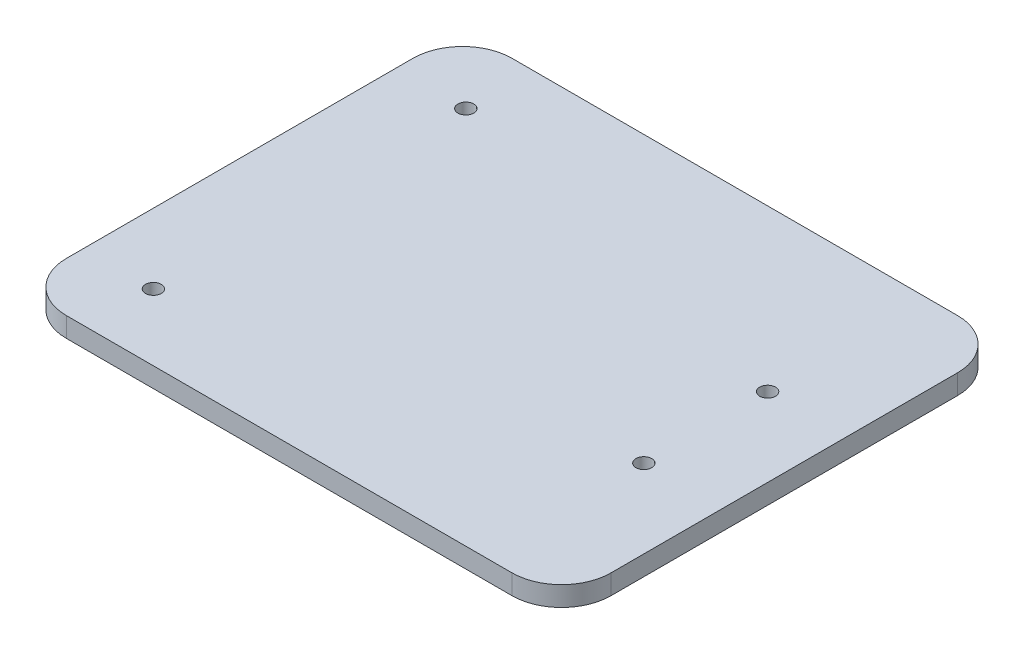
SolidWorks part; units mm, degrees
ref_plane "Front Plane" through (0, 0, 0) normal (0, 0, 1) x (1, 0, 0)
ref_plane "Top Plane" through (0, 0, 0) normal (0, 1, 0) x (1, 0, 0)
ref_plane "Right Plane" through (0, 0, 0) normal (1, 0, 0) x (0, 0, -1)
other "Configuration Table"
sketch "草图1" plane through (0, 0, 0) normal (0, 1, 0) x (1, 0, 0)
  line L1 (-37.6984, 37.1351) -> (72.3016, 37.1351)
  line L2 (-37.6984, 37.1351) -> (-37.6984, -52.8649)
  line L3 (-37.6984, -52.8649) -> (72.3016, -52.8649)
  line L4 (72.3016, 37.1351) -> (72.3016, -52.8649)
  dimension "D1" = 110
  dimension "D2" = 90
extrude "凸台-拉伸1" add sketch "草图1" along normal blind 4
fillet "圆角1" radius 10 4 edges at (-37.6984, 2, -37.1351) (72.3016, 2, -37.1351) (72.3016, 2, 52.8649) (-37.6984, 2, 52.8649)
sketch "草图2" plane through (0, 4, 0) normal (0, 1, 0) x (1, 0, 0)
  line L0 (-37.6984, -7.8649) -> (72.3016, -7.8649)
  line L1 (-37.6984, 27.1351) -> (-37.6984, -42.8649) construction
  line L2 (72.3016, -42.8649) -> (72.3016, 27.1351) construction
  line L3 (-23.5739, 23.6851) -> (-23.5739, -39.4149)
  line L4 (56.4261, 4.6351) -> (56.4261, -20.3649)
  circle A0 centre (-23.5739, 23.6851) radius 1.6
  circle A1 centre (-23.5739, -39.4149) radius 1.6
  circle A2 centre (56.4261, -20.3649) radius 1.6
  circle A3 centre (56.4261, 4.6351) radius 1.6
  point P9 (-23.5739, -7.8649)
  point P12 (56.4261, -7.8649)
  dimension "D4" = 3.2
  dimension "D5" = 3.2
  dimension "D6" = 3.2
  dimension "D7" = 3.2
  dimension "D1" = 63.1
  dimension "D2" = 25
  dimension "D3" = 80
extrude "切除-拉伸1" cut sketch "草图2" against normal blind 4
